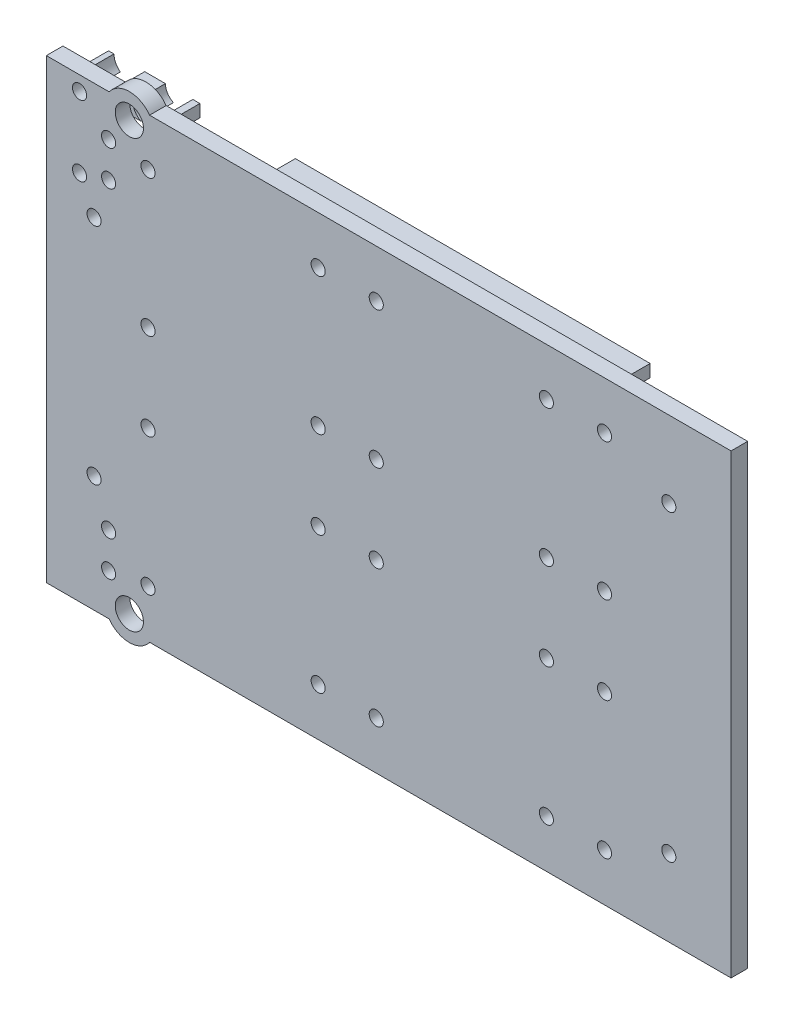
SolidWorks part; units mm, degrees
other "Platform Segment 2"
ref_plane "Front Plane" through (0, 0, 0) normal (0, 0, 1) x (1, 0, 0)
ref_plane "Top Plane" through (0, 0, 0) normal (0, 1, 0) x (1, 0, 0)
ref_plane "Right Plane" through (0, 0, 0) normal (1, 0, 0) x (0, 0, -1)
sketch3d "Main Profile Sketch datum points"
  point P0 (0, 0, 48.5)
  point P1 (10, 0, 48.5)
  point P2 (0, 10, 48.5)
ref_plane "Main Profile Sketch plane" through (0, 0, 48.5) normal (0, 0, 1) x (1, 0, 0)
sketch "Main Profile Sketch" plane through (0, 0, 48.5) normal (0, 0, 1) x (1, 0, 0)
  line L0 (-85.1266, 55) -> (55, 55)
  line L1 (55, 55) -> (55, -55)
  line L2 (-85.1266, -55) -> (55, -55)
  line L3 (-110, -55) -> (-94.8734, -55)
  line L4 (-110, 55) -> (-110, -55)
  line L5 (-110, 55) -> (-94.8734, 55)
  arc A0 (-94.8734, -55) -> (-85.1266, -55) centre (-90, -51.5) ccw
  arc A1 (-85.1266, 55) -> (-94.8734, 55) centre (-90, 51.5) ccw
  circle A2 centre (-90, -51.5) radius 3.4
  circle A3 centre (-95, -45) radius 1.7
  circle A4 centre (-85.5, -43.5) radius 1.7
  circle A5 centre (-95, -36.5) radius 1.7
  circle A6 centre (-44.5, -43.5) radius 1.7
  circle A7 centre (-30.5, -43.5) radius 1.7
  circle A8 centre (-98.5, -27) radius 1.7
  circle A9 centre (-85.5, -10.5) radius 1.7
  circle A10 centre (-44.5, -10.5) radius 1.7
  circle A11 centre (-30.5, -10.5) radius 1.7
  circle A12 centre (10.5, -43.5) radius 1.7
  circle A13 centre (24.5, -43.5) radius 1.7
  circle A14 centre (40, -36.5) radius 1.7
  circle A15 centre (10.5, -10.5) radius 1.7
  circle A16 centre (24.5, -10.5) radius 1.7
  circle A17 centre (-85.5, 10.5) radius 1.7
  circle A18 centre (-98.5, 27) radius 1.7
  circle A19 centre (-44.5, 10.5) radius 1.7
  circle A20 centre (-30.5, 10.5) radius 1.7
  circle A21 centre (-102, 34.5) radius 1.7
  circle A22 centre (-95, 36.5) radius 1.7
  circle A23 centre (-95, 45) radius 1.7
  circle A24 centre (-102, 51.5) radius 1.7
  circle A25 centre (-90, 51.5) radius 3.4
  circle A26 centre (-85.5, 43.5) radius 1.7
  circle A27 centre (-44.5, 43.5) radius 1.7
  circle A28 centre (-30.5, 43.5) radius 1.7
  circle A29 centre (10.5, 10.5) radius 1.7
  circle A30 centre (24.5, 10.5) radius 1.7
  circle A31 centre (10.5, 43.5) radius 1.7
  circle A32 centre (40, 36.5) radius 1.7
  circle A33 centre (24.5, 43.5) radius 1.7
extrude "Main Extrusion" add sketch "Main Profile Sketch" against normal blind 3.5 separate body
sketch3d "Detail Profile 2 Sketch datum points"
  point P0 (0, 0, 45)
  point P1 (10, 0, 45)
  point P2 (0, 10, 45)
ref_plane "Detail Profile 2 Sketch plane" through (0, 0, 45) normal (0, 0, 1) x (1, 0, 0)
sketch "Detail Profile 2 Sketch" plane through (0, 0, 45) normal (0, 0, 1) x (1, 0, 0)
  line L0 (-85.1266, 55) -> (55, 55)
  line L1 (55, 55) -> (55, -55)
  line L2 (-85.1266, -55) -> (55, -55)
  line L3 (-110, -55) -> (-94.8734, -55)
  line L4 (-110, 55) -> (-110, -55)
  line L5 (-110, 55) -> (-94.8734, 55)
  arc A0 (-94.8734, -55) -> (-85.1266, -55) centre (-90, -51.5) ccw
  arc A1 (-85.1266, 55) -> (-94.8734, 55) centre (-90, 51.5) ccw
  circle A2 centre (-90, -51.5) radius 5.3
  circle A3 centre (-95, -45) radius 1.7
  circle A4 centre (-85.5, -43.5) radius 1.7
  circle A5 centre (-95, -36.5) radius 1.7
  circle A6 centre (-44.5, -43.5) radius 1.7
  circle A7 centre (-30.5, -43.5) radius 1.7
  circle A8 centre (-98.5, -27) radius 1.7
  circle A9 centre (-85.5, -10.5) radius 1.7
  circle A10 centre (-44.5, -10.5) radius 1.7
  circle A11 centre (-30.5, -10.5) radius 1.7
  circle A12 centre (10.5, -43.5) radius 1.7
  circle A13 centre (24.5, -43.5) radius 1.7
  circle A14 centre (40, -36.5) radius 1.7
  circle A15 centre (10.5, -10.5) radius 1.7
  circle A16 centre (24.5, -10.5) radius 1.7
  circle A17 centre (-85.5, 10.5) radius 1.7
  circle A18 centre (-98.5, 27) radius 1.7
  circle A19 centre (-44.5, 10.5) radius 1.7
  circle A20 centre (-30.5, 10.5) radius 1.7
  circle A21 centre (-102, 34.5) radius 1.7
  circle A22 centre (-95, 36.5) radius 1.7
  circle A23 centre (-95, 45) radius 1.7
  circle A24 centre (-102, 51.5) radius 1.7
  circle A25 centre (-90, 51.5) radius 5.3
  circle A26 centre (-85.5, 43.5) radius 1.7
  circle A27 centre (-44.5, 43.5) radius 1.7
  circle A28 centre (-30.5, 43.5) radius 1.7
  circle A29 centre (10.5, 10.5) radius 1.7
  circle A30 centre (24.5, 10.5) radius 1.7
  circle A31 centre (10.5, 43.5) radius 1.7
  circle A32 centre (40, 36.5) radius 1.7
  circle A33 centre (24.5, 43.5) radius 1.7
extrude "Detail Extrusion 2" add sketch "Detail Profile 2 Sketch" against normal blind 0.5
sketch3d "Detail Profile 3 Sketch datum points"
  point P0 (0, 0, 44.5)
  point P1 (10, 0, 44.5)
  point P2 (0, 10, 44.5)
ref_plane "Detail Profile 3 Sketch plane" through (0, 0, 44.5) normal (0, 0, 1) x (1, 0, 0)
sketch "Detail Profile 3 Sketch" plane through (0, 0, 44.5) normal (0, 0, 1) x (1, 0, 0)
  line L0 (-107, -48.5) -> (-94.3692, -48.5)
  line L1 (-107, -51.5) -> (-95.3, -51.5)
  line L2 (-107, -48.5) -> (-107, -51.5)
  line L3 (-85.6308, -48.5) -> (-85, -48.5)
  line L4 (-85, -48.5) -> (-85, -49.7422)
  line L5 (-62, -48.5) -> (-62, -51.5)
  line L6 (-62, -48.5) -> (23.5, -48.5)
  line L7 (23.5, -48.5) -> (23.5, -51.5)
  line L8 (-62, -51.5) -> (23.5, -51.5)
  line L9 (-107, 51.5) -> (-105.7, 51.5)
  line L10 (-107, 48.5) -> (-104.1656, 48.5)
  line L11 (-107, 51.5) -> (-107, 48.5)
  line L12 (-98.3, 51.5) -> (-95.3, 51.5)
  line L13 (-99.8344, 48.5) -> (-94.3692, 48.5)
  line L14 (-85, 49.7422) -> (-85, 48.5)
  line L15 (-85.6308, 48.5) -> (-85, 48.5)
  line L16 (-62, 51.5) -> (-62, 48.5)
  line L17 (-62, 51.5) -> (23.5, 51.5)
  line L18 (23.5, 51.5) -> (23.5, 48.5)
  line L19 (-62, 48.5) -> (23.5, 48.5)
  arc A0 (-94.3692, -48.5) -> (-95.3, -51.5) centre (-90, -51.5) ccw
  arc A1 (-85, -49.7422) -> (-85.6308, -48.5) centre (-90, -51.5) ccw
  arc A2 (-105.7, 51.5) -> (-104.1656, 48.5) centre (-102, 51.5) ccw
  arc A3 (-99.8344, 48.5) -> (-98.3, 51.5) centre (-102, 51.5) ccw
  arc A4 (-95.3, 51.5) -> (-94.3692, 48.5) centre (-90, 51.5) ccw
  arc A5 (-85.6308, 48.5) -> (-85, 49.7422) centre (-90, 51.5) ccw
extrude "Detail Extrusion 3" add sketch "Detail Profile 3 Sketch" against normal blind 0.2
sketch3d "Detail Profile 4 Sketch datum points"
  point P0 (0, 0, 44.3)
  point P1 (10, 0, 44.3)
  point P2 (0, 10, 44.3)
ref_plane "Detail Profile 4 Sketch plane" through (0, 0, 44.3) normal (0, 0, 1) x (1, 0, 0)
sketch "Detail Profile 4 Sketch" plane through (0, 0, 44.3) normal (0, 0, 1) x (1, 0, 0)
  line L0 (-107, -48.5) -> (-91.3748, -48.5)
  line L1 (-107, -51.5) -> (-93.3, -51.5)
  line L2 (-107, -48.5) -> (-107, -51.5)
  line L3 (-85, -48.5) -> (-85, -51.5)
  line L4 (-86.7, -51.5) -> (-85, -51.5)
  line L5 (-88.6252, -48.5) -> (-85, -48.5)
  line L6 (-62, -48.5) -> (-62, -51.5)
  line L7 (-62, -48.5) -> (23.5, -48.5)
  line L8 (23.5, -48.5) -> (23.5, -51.5)
  line L9 (-62, -51.5) -> (23.5, -51.5)
  line L10 (-107, 51.5) -> (-105.7, 51.5)
  line L11 (-107, 48.5) -> (-104.1656, 48.5)
  line L12 (-107, 51.5) -> (-107, 48.5)
  line L13 (-98.3, 51.5) -> (-93.3, 51.5)
  line L14 (-99.8344, 48.5) -> (-91.3748, 48.5)
  line L15 (-86.7, 51.5) -> (-85, 51.5)
  line L16 (-85, 51.5) -> (-85, 48.5)
  line L17 (-88.6252, 48.5) -> (-85, 48.5)
  line L18 (-62, 51.5) -> (-62, 48.5)
  line L19 (-62, 51.5) -> (23.5, 51.5)
  line L20 (23.5, 51.5) -> (23.5, 48.5)
  line L21 (-62, 48.5) -> (23.5, 48.5)
  arc A0 (-91.3748, -48.5) -> (-93.3, -51.5) centre (-90, -51.5) ccw
  arc A1 (-86.7, -51.5) -> (-88.6252, -48.5) centre (-90, -51.5) ccw
  arc A2 (-105.7, 51.5) -> (-104.1656, 48.5) centre (-102, 51.5) ccw
  arc A3 (-99.8344, 48.5) -> (-98.3, 51.5) centre (-102, 51.5) ccw
  arc A4 (-93.3, 51.5) -> (-91.3748, 48.5) centre (-90, 51.5) ccw
  arc A5 (-88.6252, 48.5) -> (-86.7, 51.5) centre (-90, 51.5) ccw
extrude "Detail Extrusion 4" add sketch "Detail Profile 4 Sketch" against normal blind 7.8
